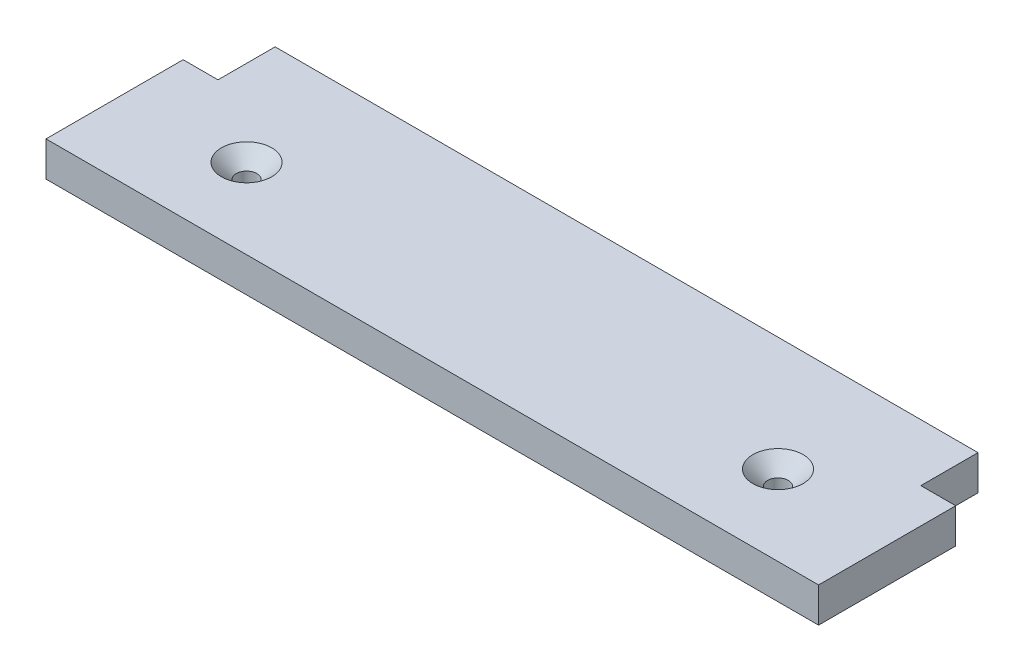
SolidWorks part; units mm, degrees
ref_plane "Front Plane" through (0, 0, 0) normal (0, 0, 1) x (1, 0, 0)
ref_plane "Top Plane" through (0, 0, 0) normal (0, 1, 0) x (1, 0, 0)
ref_plane "Right Plane" through (0, 0, 0) normal (1, 0, 0) x (0, 0, -1)
sketch "Sketch1" plane through (0, 0, 0) normal (0, 1, 0) x (1, 0, 0)
  line L0 (3.05, 12) -> (0, 7)
  line L1 (0, 0) -> (67.6, 0)
  line L2 (0, 0) -> (0, 17)
  line L3 (0, 17) -> (67.6, 17)
  line L4 (67.6, 0) -> (67.6, 17)
  line L7 (0, 12) -> (3.05, 12)
  line L8 (3.05, 17) -> (3.05, 12)
  line L11 (67.6, 12) -> (64.55, 12)
  line L12 (64.55, 17) -> (64.55, 12)
  line L13 (0, 0) -> (10.55, 0)
  line L14 (0, 0) -> (0, 7)
  line L15 (0, 7) -> (10.55, 7)
  line L16 (10.55, 0) -> (10.55, 7)
  line L17 (67.6, 0) -> (57.05, 0)
  line L18 (67.6, 0) -> (67.6, 7)
  line L19 (67.6, 7) -> (57.05, 7)
  line L20 (57.05, 0) -> (57.05, 7)
  line L21 (64.55, 12) -> (67.6, 7)
  circle A0 centre (10.55, 7) radius 0.9
  circle A1 centre (57.05, 7) radius 0.9
  dimension "D9" = 1.8
  dimension "D12" = 1.8
  dimension "D1" = 17
  dimension "D2" = 67.6
  dimension "D3" = 5
  dimension "D4" = 3.05
  dimension "D5" = 5
  dimension "D6" = 3.05
  dimension "D7" = 10.55
  dimension "D8" = 7
  dimension "D10" = 7
  dimension "D11" = 10.55
  dimension "D13" = 5
  dimension "D14" = 58.617
  dimension "D15" = 5
  dimension "D16" = 58.617
extrude "Boss-Extrude1" add sketch "Sketch1" along normal blind 3.05 contours L12 L3 L8 L7 L2 L1 L4 L11 | A0 L15 L2 L1 L16 | A1 L20 L1 L4 L19 | L11 L21 L4 | L7 L2 L0
hole_wizard "CSK for M2 Flat Head Machine Screw1" positions "Sketch4" profile "Sketch5" countersink size "M2" standard "ANSI Metric" end condition through all
sketch "Sketch4" plane through (0, 3.05, 0) normal (0, 1, 0) x (1, 0, 0)
  point P0 (10.55, 7)
sketch "Sketch5" plane through (10.55, 3.05, -7) normal (1, 0, 0) x (0, 0, 1)
  line L0 (0, 0) -> (0, 3.05)
  line L1 (0, 3.05) -> (0.9, 3.05)
  line L2 (0.9, 3.05) -> (0.9, 1.3)
  line L3 (0.9, 1.3) -> (2.2, 0)
  line L5 (2.2, 0) -> (0, 0)
  line L6 (-0.9, 1.3) -> (-2.2, 0) construction
  line L11 (0, -6.35) -> (0, 107.95) construction
  dimension "Thru Hole Dia." = 1.8
  dimension "Thru Hole Depth" = 3.05
  dimension "Near C'Sink Dia." = 4.4
  dimension "Near C'Sink Angle" = 90
hole_wizard "CSK for M2 Flat Head Machine Screw2" positions "Sketch6" profile "Sketch7" countersink size "M2" standard "ANSI Metric" end condition through all
sketch "Sketch6" plane through (0, 3.05, 0) normal (0, 1, 0) x (1, 0, 0)
  point P0 (57.05, 7)
sketch "Sketch7" plane through (57.05, 3.05, -7) normal (1, 0, 0) x (0, 0, 1)
  line L0 (0, 0) -> (0, 3.05)
  line L1 (0, 3.05) -> (0.9, 3.05)
  line L2 (0.9, 3.05) -> (0.9, 1.3)
  line L3 (0.9, 1.3) -> (2.2, 0)
  line L5 (2.2, 0) -> (0, 0)
  line L6 (-0.9, 1.3) -> (-2.2, 0) construction
  line L11 (0, -6.35) -> (0, 107.95) construction
  dimension "Thru Hole Dia." = 1.8
  dimension "Thru Hole Depth" = 3.05
  dimension "Near C'Sink Dia." = 4.4
  dimension "Near C'Sink Angle" = 90
